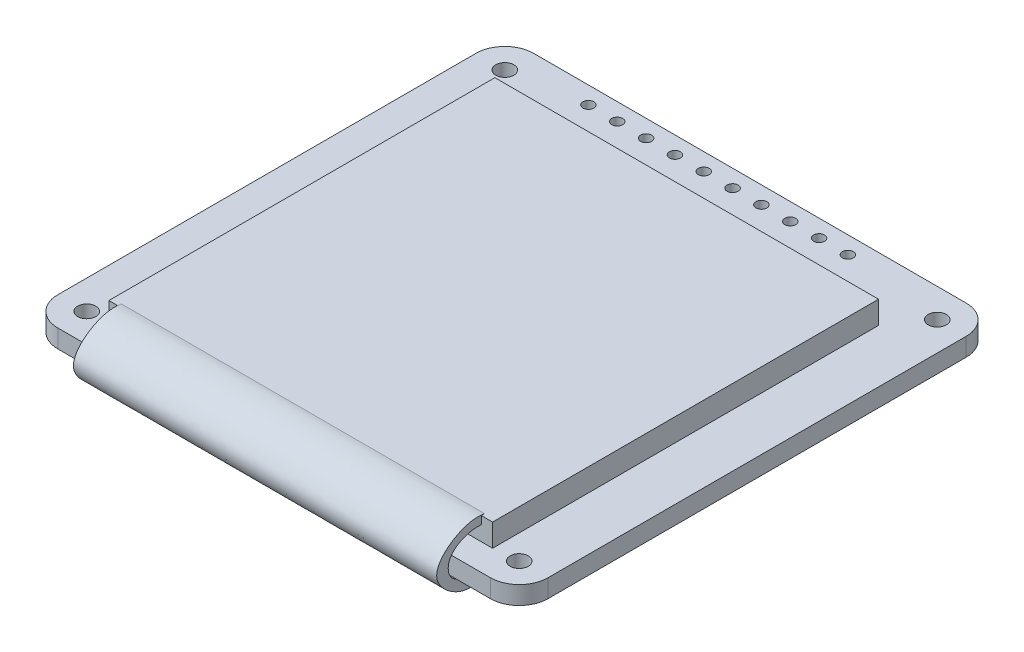
SolidWorks part; units mm, degrees
ref_plane "Front Plane" through (0, 0, 0) normal (0, 0, 1) x (1, 0, 0)
ref_plane "Top Plane" through (0, 0, 0) normal (0, 1, 0) x (1, 0, 0)
ref_plane "Right Plane" through (0, 0, 0) normal (1, 0, 0) x (0, 0, -1)
sketch "Sketch1" plane through (0, 0, 0) normal (0, 1, 0) x (1, 0, 0)
  line L0 (0, 39.37) -> (0, 2.54)
  line L1 (2.54, 0) -> (40.64, 0)
  line L2 (43.18, 2.54) -> (43.18, 39.37)
  line L3 (40.64, 41.91) -> (2.54, 41.91)
  arc A0 (0, 2.54) -> (2.54, 0) centre (2.54, 2.54) ccw
  arc A1 (40.64, 0) -> (43.18, 2.54) centre (40.64, 2.54) ccw
  arc A2 (43.18, 39.37) -> (40.64, 41.91) centre (40.64, 39.37) ccw
  arc A3 (2.54, 41.91) -> (0, 39.37) centre (2.54, 39.37) ccw
  circle A4 centre (31.75, 40.386) radius 0.4826
  circle A5 centre (31.75, 40.386) radius 0.4826
  circle A6 centre (29.21, 40.386) radius 0.4826
  circle A7 centre (29.21, 40.386) radius 0.4826
  circle A8 centre (26.67, 40.386) radius 0.4826
  circle A9 centre (26.67, 40.386) radius 0.4826
  circle A10 centre (24.13, 40.386) radius 0.4826
  circle A11 centre (24.13, 40.386) radius 0.4826
  circle A12 centre (21.59, 40.386) radius 0.4826
  circle A13 centre (21.59, 40.386) radius 0.4826
  circle A14 centre (19.05, 40.386) radius 0.4826
  circle A15 centre (19.05, 40.386) radius 0.4826
  circle A16 centre (16.51, 40.386) radius 0.4826
  circle A17 centre (16.51, 40.386) radius 0.4826
  circle A18 centre (13.97, 40.386) radius 0.4826
  circle A19 centre (13.97, 40.386) radius 0.4826
  circle A20 centre (11.43, 40.386) radius 0.4826
  circle A21 centre (11.43, 40.386) radius 0.4826
  circle A22 centre (8.89, 40.386) radius 0.4826
  circle A23 centre (8.89, 40.386) radius 0.4826
  circle A24 centre (2.54, 2.54) radius 0.8
  circle A25 centre (2.54, 2.54) radius 0.8
  circle A26 centre (40.64, 2.54) radius 0.8
  circle A27 centre (40.64, 2.54) radius 0.8
  circle A28 centre (40.64, 39.37) radius 0.8
  circle A29 centre (40.64, 39.37) radius 0.8
  circle A30 centre (2.54, 39.37) radius 0.8
  circle A31 centre (2.54, 39.37) radius 0.8
extrude "Boss-Extrude1" add sketch "Sketch1" along normal blind 1.6 contours L3 A3 L0 A0 L1 A1 L2 A2 A30 A28 A26 A24 A22 A20 A18 A16 A14 A12 A10 A8 A6 A4
sketch "Sketch2" plane through (0, 1.6, 0) normal (0, 1, 0) x (1, 0, 0)
  line L0 (0, 39.37) -> (0, 2.54) construction
  line L1 (4.69, 36.3438) -> (38.49, 36.3438)
  line L2 (4.69, 36.3438) -> (4.69, 2.3438)
  line L3 (4.69, 2.3438) -> (38.49, 2.3438)
  line L4 (38.49, 36.3438) -> (38.49, 2.3438)
  line L5 (43.18, 2.54) -> (43.18, 39.37) construction
  dimension "D1" = 33.8
  dimension "D2" = 34
  dimension "D3" = 4.69
  dimension "D4" = 4.69
extrude "Boss-Extrude2" add sketch "Sketch2" along normal blind 2
sketch "Sketch3" plane through (0, 0, 0) normal (1, 0, 0) x (0, 0, -1)
  spline S0 degree 3 poles (8.2816, -0.2295) (4.1539, 3.3516) (1.0034, 4.0569) (-2.8961, 1.1671) (0.1, -1.4379) (2.9832, -1.4241) (8.2816, -0.2295) (4.1539, 3.3516) (1.0034, 4.0569) knots -0.504023 -0.428158 -0.185343 0 0.142118 0.339134 0.495977 0.571842 0.814657 1 1.142118 1.339134 1.495977 only from (3.9702, 3.1053) to (3.9702, 3.1053)
  spline S1 degree 3 poles (5.1576, 1.2954) (3.6929, 2.6724) (1.536, 3.293) (-0.8599, 1.8627) (-0.4616, 0.1711) (1.129, -0.6658) (3.1681, -0.4896) (4.995, 0.0056) (5.1576, 1.2954) (3.6929, 2.6724) (1.536, 3.293) knots -0.252278 -0.209355 -0.084678 0 0.200569 0.386571 0.476144 0.515166 0.747722 0.790645 0.915322 1 1.200569 1.386571 1.476144 only from (4.0818, 2.2318) to (4.0818, 2.2318)
extrude "Boss-Extrude3" add sketch "Sketch3" along normal blind 32 from offset 5.5
